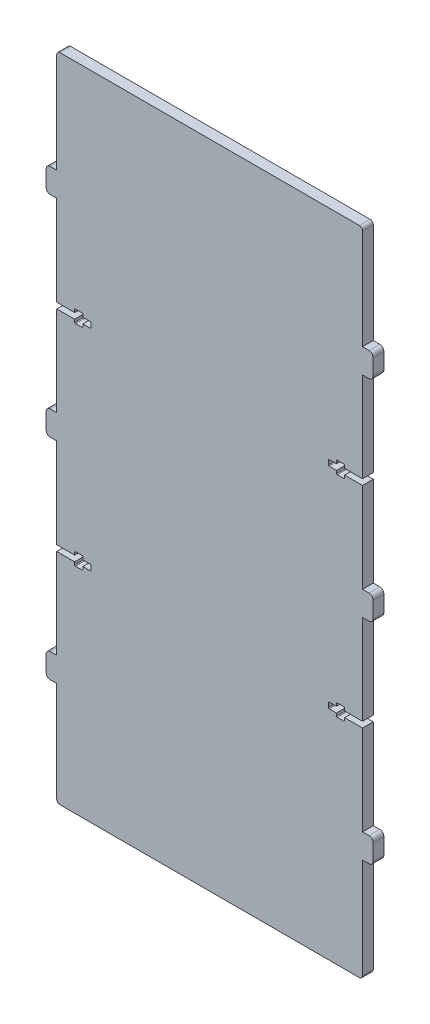
SolidWorks part; units mm, degrees
ref_plane "Front Plane" through (0, 0, 0) normal (0, 0, 1) x (1, 0, 0)
ref_plane "Top Plane" through (0, 0, 0) normal (0, 1, 0) x (1, 0, 0)
ref_plane "Right Plane" through (0, 0, 0) normal (1, 0, 0) x (0, 0, -1)
sketch "Model" plane through (0, 0, 0) normal (0, 0, 1) x (1, 0, 0)
  line L0 (-6.5, 76) -> (-6.5, 66)
  line L1 (11, 133.7375) -> (0, 133.7375)
  line L2 (11, 132.1525) -> (11, 133.7375)
  line L3 (15.5, 131.6525) -> (11.5, 131.6525)
  line L4 (16, 133.7375) -> (16, 132.1525)
  line L5 (20.5, 133.7375) -> (16, 133.7375)
  line L6 (21, 136.7875) -> (21, 134.2375)
  line L7 (16, 137.2875) -> (20.5, 137.2875)
  line L8 (16, 138.8725) -> (16, 137.2875)
  line L9 (11.5, 139.3725) -> (15.5, 139.3725)
  line L10 (11, 137.2875) -> (11, 138.8725)
  line L11 (0, 137.2875) -> (11, 137.2875)
  line L12 (0, 192.525) -> (0, 137.2875)
  line L13 (-4, 192.525) -> (0, 192.525)
  line L14 (-6.5, 205.025) -> (-6.5, 195.025)
  line L15 (0, 207.525) -> (-4, 207.525)
  line L16 (0, 262.7625) -> (0, 207.525)
  line L17 (11, 262.7625) -> (0, 262.7625)
  line L18 (11, 261.1775) -> (11, 262.7625)
  line L19 (15.5, 260.6775) -> (11.5, 260.6775)
  line L20 (16, 262.7625) -> (16, 261.1775)
  line L21 (20.5, 262.7625) -> (16, 262.7625)
  line L22 (21, 265.8125) -> (21, 263.2625)
  line L23 (16, 266.3125) -> (20.5, 266.3125)
  line L24 (16, 267.8975) -> (16, 266.3125)
  line L25 (11.5, 268.3975) -> (15.5, 268.3975)
  line L26 (11, 266.3125) -> (11, 267.8975)
  line L27 (0, 266.3125) -> (11, 266.3125)
  line L28 (0, 321.55) -> (0, 266.3125)
  line L29 (-4, 321.55) -> (0, 321.55)
  line L30 (-6.5, 334.05) -> (-6.5, 324.05)
  line L31 (0, 336.55) -> (-4, 336.55)
  line L32 (0, 398.05) -> (0, 336.55)
  line L33 (185.8, 400.05) -> (2, 400.05)
  line L34 (187.8, 336.55) -> (187.8, 398.05)
  line L35 (194.3, 324.05) -> (194.3, 334.05)
  line L36 (187.8, 266.3125) -> (187.8, 321.55)
  line L37 (176.8, 266.3125) -> (187.8, 266.3125)
  line L38 (176.8, 267.8975) -> (176.8, 266.3125)
  line L39 (172.3, 268.3975) -> (176.3, 268.3975)
  line L40 (171.8, 266.3125) -> (171.8, 267.8975)
  line L41 (167.3, 266.3125) -> (171.8, 266.3125)
  line L42 (166.8, 263.2625) -> (166.8, 265.8125)
  line L43 (171.8, 262.7625) -> (167.3, 262.7625)
  line L44 (171.8, 261.1775) -> (171.8, 262.7625)
  line L45 (176.3, 260.6775) -> (172.3, 260.6775)
  line L46 (176.8, 262.7625) -> (176.8, 261.1775)
  line L47 (187.8, 262.7625) -> (176.8, 262.7625)
  line L48 (187.8, 207.525) -> (187.8, 262.7625)
  line L49 (191.8, 207.525) -> (187.8, 207.525)
  line L50 (194.3, 195.025) -> (194.3, 205.025)
  line L51 (187.8, 192.525) -> (191.8, 192.525)
  line L52 (187.8, 137.2875) -> (187.8, 192.525)
  line L53 (176.8, 137.2875) -> (187.8, 137.2875)
  line L54 (176.8, 138.8725) -> (176.8, 137.2875)
  line L55 (172.3, 139.3725) -> (176.3, 139.3725)
  line L56 (171.8, 137.2875) -> (171.8, 138.8725)
  line L57 (167.3, 137.2875) -> (171.8, 137.2875)
  line L58 (166.8, 134.2375) -> (166.8, 136.7875)
  line L59 (171.8, 133.7375) -> (167.3, 133.7375)
  line L60 (171.8, 132.1525) -> (171.8, 133.7375)
  line L61 (176.3, 131.6525) -> (172.3, 131.6525)
  line L62 (176.8, 133.7375) -> (176.8, 132.1525)
  line L63 (187.8, 133.7375) -> (176.8, 133.7375)
  line L64 (187.8, 78.5) -> (187.8, 133.7375)
  line L65 (191.8, 78.5) -> (187.8, 78.5)
  line L66 (194.3, 66) -> (194.3, 76)
  line L67 (187.8, 63.5) -> (191.8, 63.5)
  line L68 (187.8, 2) -> (187.8, 63.5)
  line L69 (2, 0) -> (185.8, 0)
  line L70 (0, 63.5) -> (0, 2)
  line L71 (0, 78.5) -> (-4, 78.5)
  line L72 (-4, 63.5) -> (0, 63.5)
  line L73 (191.8, 336.55) -> (187.8, 336.55)
  line L74 (0, 133.7375) -> (0, 78.5)
  line L75 (187.8, 321.55) -> (191.8, 321.55)
  arc A0 (-6.5, 66) -> (-4, 63.5) centre (-4, 66) ccw
  arc A1 (-4, 78.5) -> (-6.5, 76) centre (-4, 76) ccw
  arc A2 (11, 132.1525) -> (11.5, 131.6525) centre (11.5, 132.1525) ccw
  arc A3 (15.5, 131.6525) -> (16, 132.1525) centre (15.5, 132.1525) ccw
  arc A4 (20.5, 133.7375) -> (21, 134.2375) centre (20.5, 134.2375) ccw
  arc A5 (21, 136.7875) -> (20.5, 137.2875) centre (20.5, 136.7875) ccw
  arc A6 (16, 138.8725) -> (15.5, 139.3725) centre (15.5, 138.8725) ccw
  arc A7 (11.5, 139.3725) -> (11, 138.8725) centre (11.5, 138.8725) ccw
  arc A8 (-6.5, 195.025) -> (-4, 192.525) centre (-4, 195.025) ccw
  arc A9 (-4, 207.525) -> (-6.5, 205.025) centre (-4, 205.025) ccw
  arc A10 (11, 261.1775) -> (11.5, 260.6775) centre (11.5, 261.1775) ccw
  arc A11 (15.5, 260.6775) -> (16, 261.1775) centre (15.5, 261.1775) ccw
  arc A12 (20.5, 262.7625) -> (21, 263.2625) centre (20.5, 263.2625) ccw
  arc A13 (21, 265.8125) -> (20.5, 266.3125) centre (20.5, 265.8125) ccw
  arc A14 (16, 267.8975) -> (15.5, 268.3975) centre (15.5, 267.8975) ccw
  arc A15 (11.5, 268.3975) -> (11, 267.8975) centre (11.5, 267.8975) ccw
  arc A16 (-6.5, 324.05) -> (-4, 321.55) centre (-4, 324.05) ccw
  arc A17 (-4, 336.55) -> (-6.5, 334.05) centre (-4, 334.05) ccw
  arc A18 (2, 400.05) -> (0, 398.05) centre (2, 398.05) ccw
  arc A19 (187.8, 398.05) -> (185.8, 400.05) centre (185.8, 398.05) ccw
  arc A20 (194.3, 334.05) -> (191.8, 336.55) centre (191.8, 334.05) ccw
  arc A21 (191.8, 321.55) -> (194.3, 324.05) centre (191.8, 324.05) ccw
  arc A22 (176.8, 267.8975) -> (176.3, 268.3975) centre (176.3, 267.8975) ccw
  arc A23 (172.3, 268.3975) -> (171.8, 267.8975) centre (172.3, 267.8975) ccw
  arc A24 (167.3, 266.3125) -> (166.8, 265.8125) centre (167.3, 265.8125) ccw
  arc A25 (166.8, 263.2625) -> (167.3, 262.7625) centre (167.3, 263.2625) ccw
  arc A26 (171.8, 261.1775) -> (172.3, 260.6775) centre (172.3, 261.1775) ccw
  arc A27 (176.3, 260.6775) -> (176.8, 261.1775) centre (176.3, 261.1775) ccw
  arc A28 (194.3, 205.025) -> (191.8, 207.525) centre (191.8, 205.025) ccw
  arc A29 (191.8, 192.525) -> (194.3, 195.025) centre (191.8, 195.025) ccw
  arc A30 (176.8, 138.8725) -> (176.3, 139.3725) centre (176.3, 138.8725) ccw
  arc A31 (172.3, 139.3725) -> (171.8, 138.8725) centre (172.3, 138.8725) ccw
  arc A32 (167.3, 137.2875) -> (166.8, 136.7875) centre (167.3, 136.7875) ccw
  arc A33 (166.8, 134.2375) -> (167.3, 133.7375) centre (167.3, 134.2375) ccw
  arc A34 (171.8, 132.1525) -> (172.3, 131.6525) centre (172.3, 132.1525) ccw
  arc A35 (176.3, 131.6525) -> (176.8, 132.1525) centre (176.3, 132.1525) ccw
  arc A36 (194.3, 76) -> (191.8, 78.5) centre (191.8, 76) ccw
  arc A37 (191.8, 63.5) -> (194.3, 66) centre (191.8, 66) ccw
  arc A38 (185.8, 0) -> (187.8, 2) centre (185.8, 2) ccw
  arc A39 (0, 2) -> (2, 0) centre (2, 2) ccw
extrude "Boss-Extrude1" add sketch "Model" along normal blind 6.6
